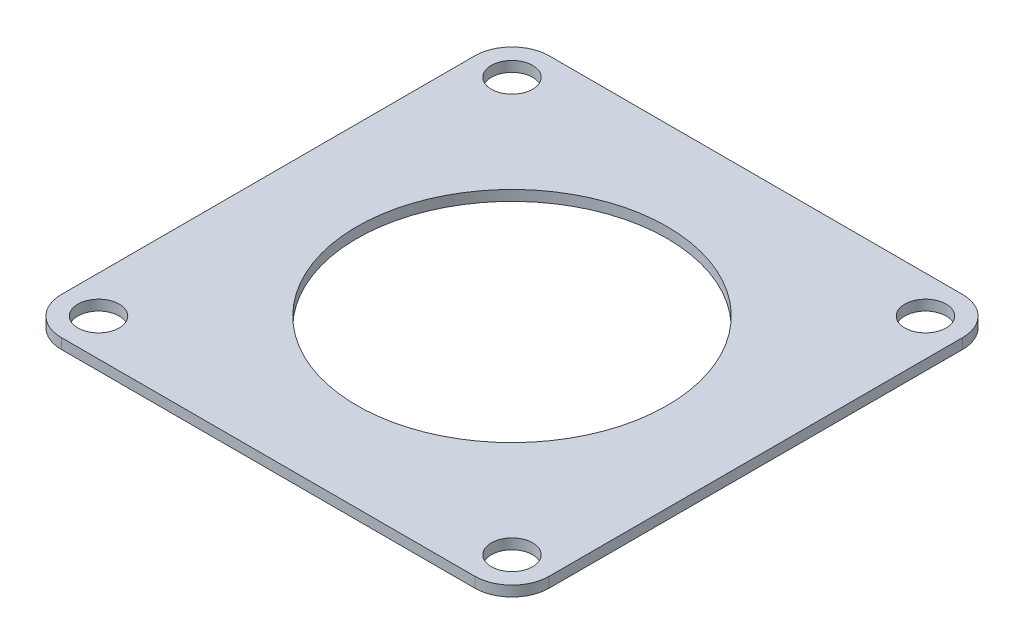
SolidWorks part; units mm, degrees
ref_plane "Front" through (0, 0, 0) normal (0, 0, 1) x (1, 0, 0)
ref_plane "Top" through (0, 0, 0) normal (0, 1, 0) x (1, 0, 0)
ref_plane "Right" through (0, 0, 0) normal (1, 0, 0) x (0, 0, -1)
sketch "草图1" plane through (0, 0, 0) normal (0, 1, 0) x (1, 0, 0)
  line L0 (-100, 118) -> (100, 118)
  line L5 (-100, 100) -> (0, 0) construction
  line L6 (-92.9289, -92.9289) -> (100, 100) construction
  line L7 (118, 100) -> (118, -100)
  line L8 (100, -118) -> (-100, -118)
  line L9 (-118, -100) -> (-118, 100)
  line L13 (87.2721, -87.2721) -> (92.9289, -92.9289) construction
  circle A0 centre (100, 100) radius 10
  circle A1 centre (100, -100) radius 10
  circle A2 centre (-100, -100) radius 10
  circle A3 centre (-100, 100) radius 10
  arc A5 (-100, 118) -> (-118, 100) centre (-100, 100) ccw
  arc A6 (118, 100) -> (100, 118) centre (100, 100) ccw
  arc A7 (100, -118) -> (118, -100) centre (100, -100) ccw
  arc A8 (-118, -100) -> (-100, -118) centre (-100, -100) ccw
  circle A9 centre (-100, 100) radius 18 construction
  point P0 (0, 0)
  point P16 (0, 0)
  point P24 (0, 0)
  point P34 (0, 0)
  dimension "D3" = 20
  dimension "D2" = 200
  dimension "D5" = 8
  dimension "D4" = 4
  dimension "D6" = 4
  dimension "D7" = 4
extrude "凸台-拉伸1" add sketch "草图1" along normal blind 5
sketch "草图2" plane through (0, 0, 0) normal (0, -1, 0) x (1, 0, 0)
  circle A0 centre (0, 0) radius 75
  dimension "D1" = 150
extrude "切除-拉伸1" cut sketch "草图2" against normal through all
